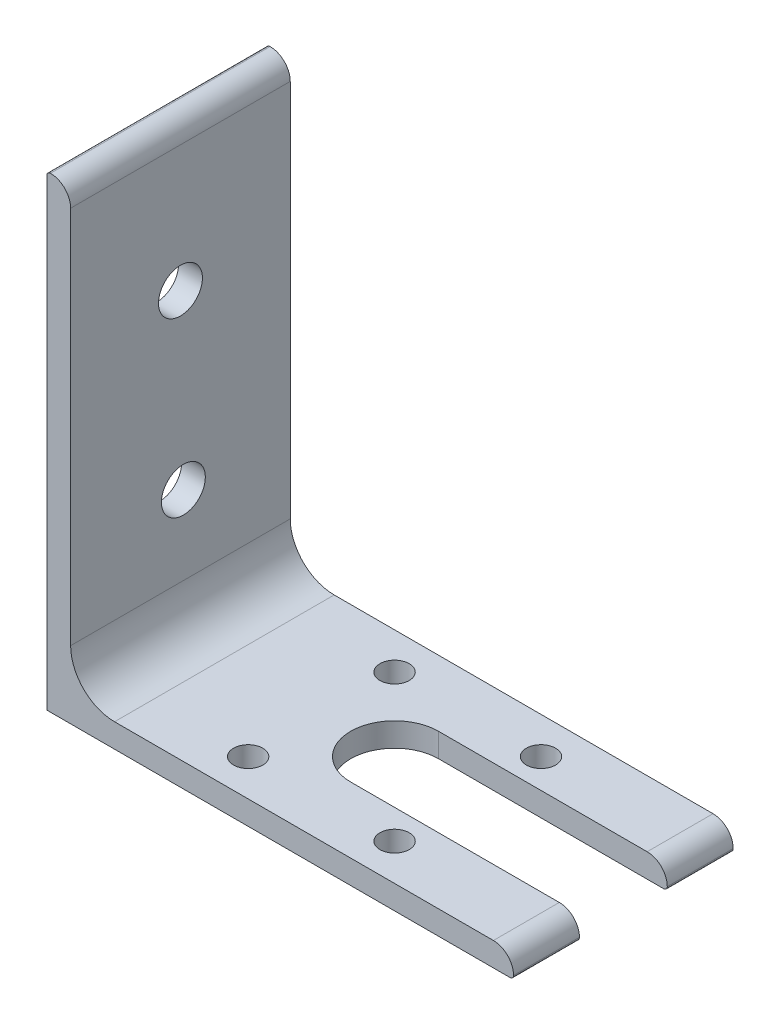
SolidWorks part; units mm, degrees
ref_plane "Front Plane" through (0, 0, 0) normal (0, 0, 1) x (1, 0, 0)
ref_plane "Top Plane" through (0, 0, 0) normal (0, 1, 0) x (1, 0, 0)
ref_plane "Right Plane" through (0, 0, 0) normal (1, 0, 0) x (0, 0, -1)
sketch "Sketch2" plane through (0, 0, 0) normal (0, 0, 1) x (1, 0, 0)
  line L0 (0, 0) -> (63.26, 0)
  line L1 (0, 0) -> (0, 63.26)
  line L2 (0.49, 63.75) -> (0.5, 63.75)
  line L3 (3.25, 61) -> (3.25, 9.25)
  line L4 (9.25, 3.25) -> (61, 3.25)
  line L5 (63.75, 0.5) -> (63.75, 0.49)
  arc A0 (9.25, 3.25) -> (3.25, 9.25) centre (9.25, 9.25) cw
  arc A1 (3.25, 61) -> (0.5, 63.75) centre (0.5, 61) ccw
  arc A2 (0.49, 63.75) -> (0, 63.26) centre (0.49, 63.26) ccw
  arc A3 (63.75, 0.5) -> (61, 3.25) centre (61, 0.5) ccw
  arc A4 (63.26, 0) -> (63.75, 0.49) centre (63.26, 0.49) ccw
  point P11 (3.25, 63.75)
  point P14 (0, 63.75)
  point P17 (63.75, 3.25)
  point P20 (63.75, 0)
  dimension "D5" = 6
  dimension "D6" = 2.75
  dimension "D7" = 0.49
  dimension "D8" = 2.75
  dimension "D9" = 0.49
  dimension "D1" = 63.75
  dimension "D2" = 63.75
  dimension "D3" = 3.25
  dimension "D4" = 3.25
extrude "Boss-Extrude1" add sketch "Sketch2" against normal blind 30
sketch "Sketch3" plane through (0, 3.25, 0) normal (0, 1, 0) x (1, 0, 0)
  point P0 (22.5, 5)
  point P1 (22.5, 25)
  point P3 (42.5, 25)
  point P5 (42.5, 5)
hole_wizard "Ø4.0 (4) Diameter Hole1" positions "Sketch5" profile "Sketch4" hole size "Ø4.0" standard "ANSI Metric"
sketch "Sketch5" plane through (0, 3.25, 0) normal (0, 1, 0) x (1, 0, 0)
  line L1 (22.5, 25) -> (42.5, 5) construction
  line L2 (42.5, 25) -> (22.5, 5) construction
  point P0 (22.5, 5)
  point P3 (22.5, 25)
  point P6 (42.5, 25)
  point P9 (42.5, 5)
sketch "Sketch4" plane through (22.5, 3.25, -5) normal (1, 0, 0) x (0, 0, 1)
  line L0 (0, 0) -> (0, 11.2017)
  line L1 (0, 11.2017) -> (2, 10)
  line L2 (2, 10) -> (2, 0)
  line L5 (2, 0) -> (0, 0)
  line L10 (0, 11.2017) -> (-2, 10) construction
  line L11 (0, -6.35) -> (0, 107.95) construction
  dimension "Hole Dia." = 4
  dimension "Hole Depth" = 10
  dimension "Drill Angle" = 118
sketch "Sketch6" plane through (0, 3.25, 0) normal (0, 1, 0) x (1, 0, 0)
  line L0 (22.5, 25) -> (36.7426, 10.7574) construction
  line L1 (22.5, 5) -> (36.7426, 19.2426) construction
  line L2 (32.5, 9) -> (66.8673, 9)
  line L3 (32.5, 21) -> (66.8673, 21)
  line L4 (66.8673, 21) -> (66.8673, 9)
  line L5 (38.5, 21) -> (42.5, 25) construction
  line L6 (38.5, 9) -> (42.5, 5) construction
  arc A0 (32.5, 21) -> (32.5, 9) centre (32.5, 15) ccw
extrude "Cut-Extrude1" cut sketch "Sketch6" against normal through all
sketch "Sketch7" plane through (3.25, 0, 0) normal (1, 0, 0) x (0, 0, -1)
  line L0 (0, 9.25) -> (0, 61) construction
  line L2 (30, 63.75) -> (0, 63.75) construction
  line L3 (30, 0) -> (0, 0) construction
  point P0 (15, 43.75)
  point P1 (15.3992, 20)
  dimension "D1" = 15
  dimension "D2" = 20
  dimension "D3" = 20
hole_wizard "Ø6.0 (6) Diameter Hole1" positions "Sketch9" profile "Sketch8" hole size "Ø6.0" standard "ANSI Metric"
sketch "Sketch9" plane through (3.25, 0, 0) normal (1, 0, 0) x (0, 0, -1)
  point P0 (15, 43.75)
  point P3 (15.3992, 20)
sketch "Sketch8" plane through (3.25, 43.75, -15) normal (0, 1, 0) x (0, 0, -1)
  line L0 (0, 0) -> (0, 11.8026)
  line L1 (0, 11.8026) -> (3, 10)
  line L2 (3, 10) -> (3, 0)
  line L5 (3, 0) -> (0, 0)
  line L10 (0, 11.8026) -> (-3, 10) construction
  line L11 (0, -6.35) -> (0, 107.95) construction
  dimension "Hole Dia." = 6
  dimension "Hole Depth" = 10
  dimension "Drill Angle" = 118
